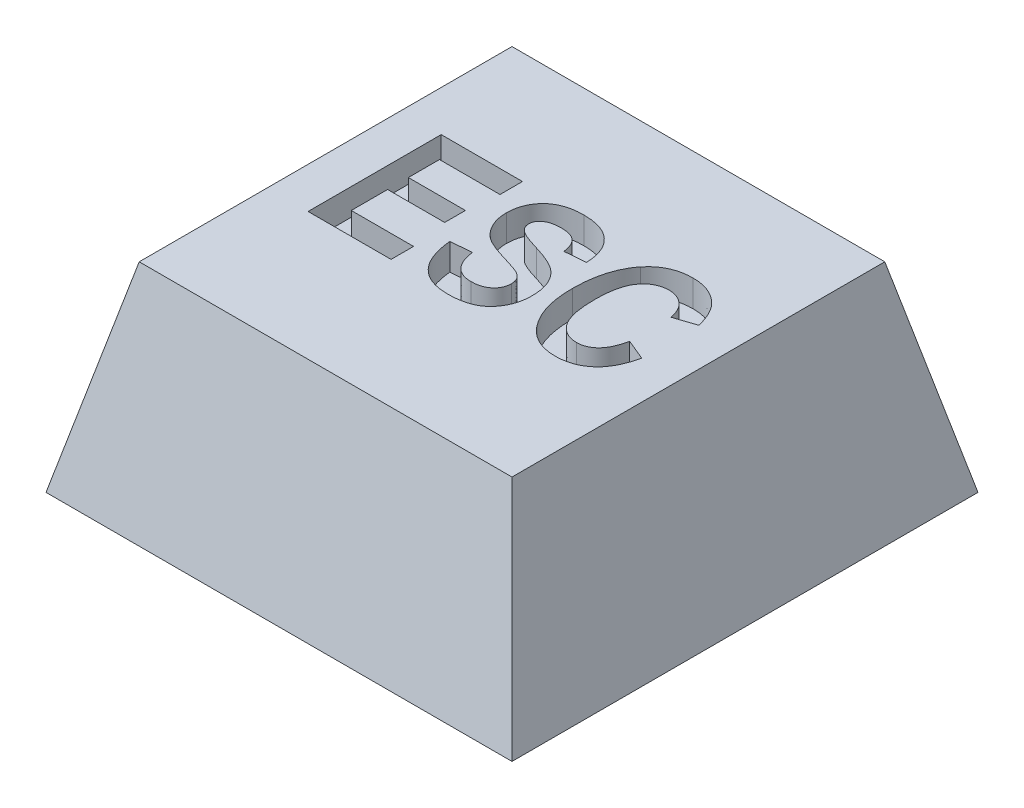
SolidWorks part; units mm, degrees
ref_plane "Front Plane" through (0, 0, 0) normal (0, 0, 1) x (1, 0, 0)
ref_plane "Top Plane" through (0, 0, 0) normal (0, 1, 0) x (1, 0, 0)
ref_plane "Right Plane" through (0, 0, 0) normal (1, 0, 0) x (0, 0, -1)
sketch "Sketch1" plane through (0, 0, 0) normal (0, 1, 0) x (1, 0, 0)
  line L1 (0, 0) -> (7, 0)
  line L2 (0, 0) -> (0, 7)
  line L3 (0, 7) -> (7, 7)
  line L4 (7, 0) -> (7, 7)
  dimension "D1" = 7
  dimension "D2" = 7
extrude "Boss-Extrude1" add sketch "Sketch1" along normal blind 3
sketch "Sketch2" plane through (0, 0, 0) normal (0, 0, 1) x (1, 0, 0)
  line L0 (0, 0) -> (0.7, 3)
  line L1 (0, 3) -> (7, 3) construction
  line L2 (0.7, 3) -> (0, 3)
  line L3 (0, 3) -> (0, 0)
  line L4 (7, 0) -> (6.3, 3)
  line L5 (6.3, 3) -> (7, 3)
  line L6 (7, 3) -> (7, 0)
  dimension "D1" = 0.7
  dimension "D2" = 0.7
extrude "Cut-Extrude1" cut sketch "Sketch2" against normal blind 7
sketch "Sketch3" plane through (0, 0, 0) normal (1, 0, 0) x (0, 0, -1)
  line L0 (0, 0) -> (0.7, 3)
  line L1 (7, 3) -> (0, 3) construction
  line L2 (0.7, 3) -> (0, 3)
  line L3 (0, 3) -> (0, 0)
  line L4 (7, 3) -> (6.3, 3)
  line L5 (6.3, 3) -> (7, 0)
  line L6 (7, 3) -> (7, 0)
  dimension "D1" = 0.7
  dimension "D2" = 0.7
extrude "Cut-Extrude2" cut sketch "Sketch3" along normal blind 11
sketch "Sketch4" plane through (0, 0, 0) normal (0, -1, 0) x (1, 0, 0)
  line L0 (3.5, 0) -> (3.5, -7) construction
  line L1 (0, 0) -> (7, 0) construction
  line L2 (7, -7) -> (0, -7) construction
  line L3 (0, -3.5) -> (7, -3.5) construction
  line L4 (0, -7) -> (0, 0) construction
  line L5 (7, 0) -> (7, -7) construction
  circle A0 centre (3.5, -3.5) radius 1.8
  dimension "D1" = 3.6
extrude "Cut-Extrude3" cut sketch "Sketch4" against normal blind 0.8
sketch "Sketch5" plane through (0, 3, 0) normal (0, 1, 0) x (1, 0, 0)
  text T0 "<b>ESC</b>" font "Arial Narrow" height 2
extrude "Cut-Extrude4" cut sketch "Sketch5" against normal blind 0.4
